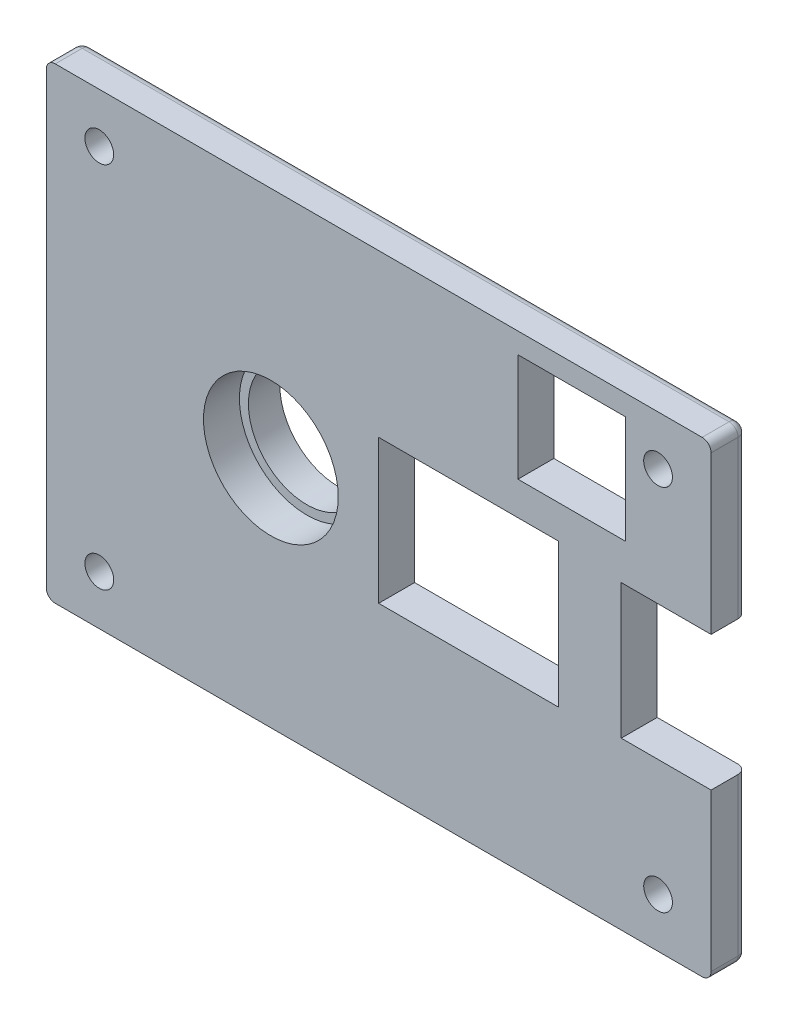
SolidWorks part; units mm, degrees
ref_plane "Front Plane" through (0, 0, 0) normal (0, 0, 1) x (1, 0, 0)
ref_plane "Top Plane" through (0, 0, 0) normal (0, 1, 0) x (1, 0, 0)
ref_plane "Right Plane" through (0, 0, 0) normal (1, 0, 0) x (0, 0, -1)
sketch "Enclosure Top Sketch" plane through (0, 0, 0) normal (0, 0, 1) x (1, 0, 0)
  line L1 (-37, 26) -> (37, 26)
  line L2 (-37, 26) -> (-37, -26)
  line L3 (-37, -26) -> (37, -26)
  line L4 (37, 26) -> (37, -26)
  line L5 (-37, 26) -> (37, -26) construction
  line L6 (-37, -26) -> (37, 26) construction
  point P1 (0, 0)
  dimension "D1" = 52
  dimension "D2" = 74
extrude "Enclosure Top Feature" add sketch "Enclosure Top Sketch" along normal blind 4
sketch "Screw Holes Sketch" plane through (0, 0, 4) normal (0, 0, 1) x (1, 0, 0)
  line L4 (-37, 26) -> (-37, -26) construction
  line L5 (37, 26) -> (-37, 26) construction
  line L6 (37, -26) -> (37, 26) construction
  line L7 (-37, -26) -> (37, -26) construction
  circle A0 centre (-31.1, 20.5) radius 1.6
  circle A1 centre (31.096, 20.5) radius 1.6
  circle A2 centre (31.1, -20.5) radius 1.6
  circle A3 centre (-31.096, -20.5) radius 1.6
  dimension "D1" = 5.9
  dimension "D3" = 62.196
  dimension "D4" = 5.9
  dimension "D5" = 5.5
  dimension "D6" = 62.196
  dimension "D2" = 5.5
extrude "Screw Holes Feature" cut sketch "Screw Holes Sketch" against normal through all
sketch "Camera + Light Hole Sketch" plane through (0, 0, 4) normal (0, 0, 1) x (1, 0, 0)
  line L0 (37, -26) -> (37, 26) construction
  line L5 (-37, 26) -> (-37, -26) construction
  line L6 (-37, -26) -> (37, -26) construction
  line L7 (0, 8) -> (20, 8)
  line L8 (0, 8) -> (0, -8)
  line L9 (0, -8) -> (20, -8)
  line L10 (20, 8) -> (20, -8)
  line L11 (0, 8) -> (20, -8) construction
  line L12 (0, -8) -> (20, 8) construction
  line L13 (27, 7.5) -> (37, 7.5)
  line L14 (27, 7.5) -> (27, -7.5)
  line L15 (27, -7.5) -> (37, -7.5)
  line L16 (37, 7.5) -> (37, -7.5)
  line L17 (27, 7.5) -> (37, -7.5) construction
  line L18 (27, -7.5) -> (37, 7.5) construction
  line L19 (37, 26) -> (-37, 26) construction
  line L20 (15.5, 23.714) -> (27.5, 23.714)
  line L21 (15.5, 23.714) -> (15.5, 11.714)
  line L22 (15.5, 11.714) -> (27.5, 11.714)
  line L23 (27.5, 23.714) -> (27.5, 11.714)
  line L24 (15.5, 23.714) -> (27.5, 11.714) construction
  line L25 (15.5, 11.714) -> (27.5, 23.714) construction
  circle A2 centre (-12, 0) radius 7.5
  point P5 (10, 0)
  point P11 (32, 0)
  point P13 (21.5, 17.714)
  dimension "D1" = 25
  dimension "D8" = 15
  dimension "D9" = 10
  dimension "D2" = 26
  dimension "D3" = 16
  dimension "D4" = 20
  dimension "D5" = 22
  dimension "D6" = 0
  dimension "D7" = 0
  dimension "D10" = 0
  dimension "D11" = 9.5
  dimension "D12" = 2.286
  dimension "D13" = 12
  dimension "D14" = 12
extrude "Camera + Light Hole Feature " cut sketch "Camera + Light Hole Sketch" against normal through all
sketch "Filter Cover Sketch" plane through (0, 0, 0) normal (0, 0, -1) x (-1, 0, 0)
  circle A0 centre (12, 0) radius 9
extrude "Filter Cover Feature" add sketch "Filter Cover Sketch" along normal blind 3.5
sketch "Filter Cut Sketch" plane through (0, 0, -3.5) normal (0, 0, -1) x (-1, 0, 0)
  circle A0 centre (12, 0) radius 6.5
extrude "Filter Cut" cut sketch "Filter Cut Sketch" against normal blind 3.5
fillet "Fillet1" radius 1 1 edges at (0, 26, 0)
fillet "Fillet2" radius 1 3 edges at (-37, 26, 2.5) (-37, 25.7071, 0.2929) (-37, -0.5, 0)
fillet "Fillet3" radius 1 3 edges at (-37, -26, 2.5) (-36.7071, -26, 0.2929) (0.5, -26, 0)
fillet "Fillet4" radius 1 3 edges at (37, -26, 2.5) (37, -25.7071, 0.2929) (37, -16.25, 0)
fillet "Fillet5" radius 1 3 edges at (37, 26, 2.5) (37, 25.7071, 0.2929) (37, 16.25, 0)
fillet "Fillet6" radius 1 1 edges at (-21, 0, -3.5)
